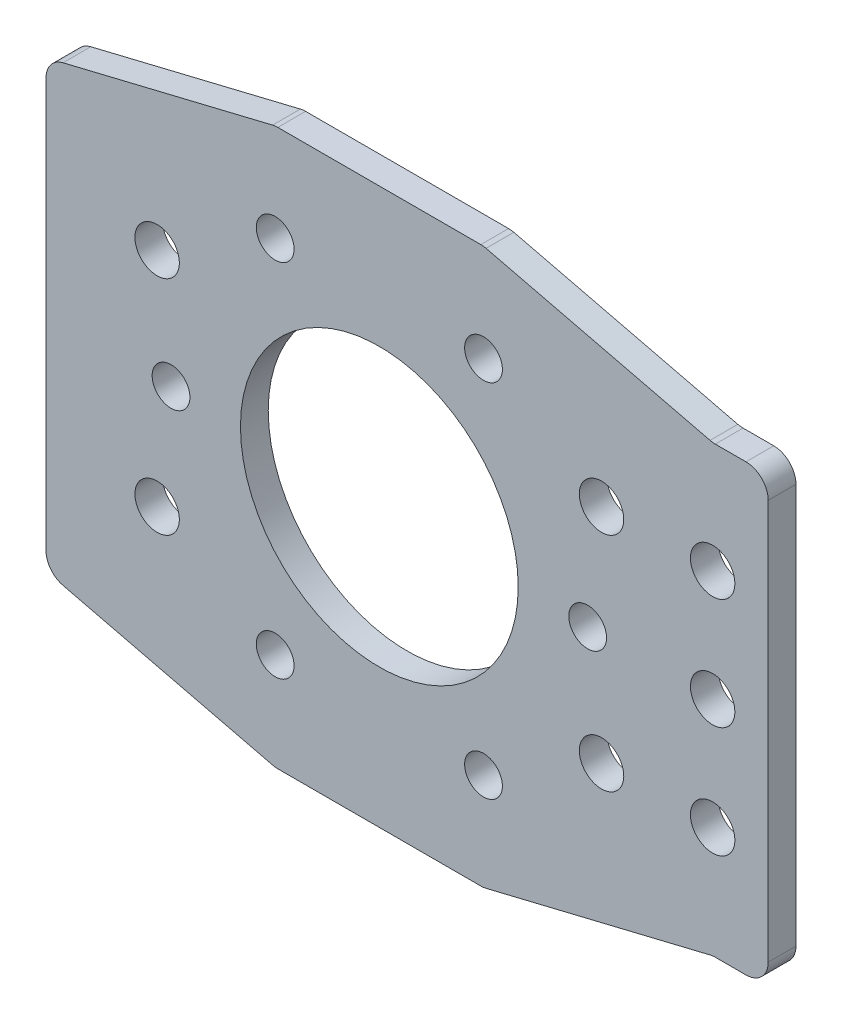
SolidWorks part; units mm, degrees
ref_plane "Front Plane" through (0, 0, 0) normal (0, 0, 1) x (1, 0, 0)
ref_plane "Top Plane" through (0, 0, 0) normal (0, 1, 0) x (1, 0, 0)
ref_plane "Right Plane" through (0, 0, 0) normal (1, 0, 0) x (0, 0, -1)
sketch "Sketch1" plane through (0, 0, 0) normal (0, 0, 1) x (1, 0, 0)
  arc A19 (-480.6, -14.2) -> (-459.2, -14.2) centre (-469.9, 0) ccw
  arc A20 (-446.9968, 12.573) -> (-442.0032, 12.573) centre (-444.5, 12.7) ccw
  arc A21 (-421.5968, 12.573) -> (-416.6032, 12.573) centre (-419.1, 12.7) ccw
  arc A22 (-434.2968, 12.573) -> (-429.3032, 12.573) centre (-431.8, 12.7) ccw
  arc A23 (-434.2968, -0.127) -> (-429.3032, -0.127) centre (-431.8, 0) ccw
  arc A24 (-421.5968, -0.127) -> (-416.6032, -0.127) centre (-419.1, 0) ccw
  arc A25 (-421.5968, -12.827) -> (-416.6032, -12.827) centre (-419.1, -12.7) ccw
  arc A26 (-434.2968, -12.827) -> (-429.3032, -12.827) centre (-431.8, -12.7) ccw
  arc A27 (-446.9968, -12.827) -> (-442.0032, -12.827) centre (-444.5, -12.7) ccw
  arc A28 (-491.5572, 0.127) -> (-494.0059, 2.139) centre (-493.7125, 0) ccw
  arc A29 (-494.0059, -2.139) -> (-491.5572, -0.127) centre (-493.7125, 0) ccw
  arc A30 (-497.7968, 12.573) -> (-492.8032, 12.573) centre (-495.3, 12.7) ccw
  arc A31 (-497.7968, -12.827) -> (-492.8032, -12.827) centre (-495.3, -12.7) ccw
  circle A32 centre (-481.8062, -20.6222) radius 2.159
  circle A33 centre (-457.9938, -20.6222) radius 2.159
  arc A34 (-448.2428, -0.127) -> (-445.7941, -2.139) centre (-446.0875, 0) ccw
  arc A35 (-445.7941, 2.139) -> (-448.2428, 0.127) centre (-446.0875, 0) ccw
  circle A36 centre (-457.9937, 20.6222) radius 2.159
  circle A37 centre (-481.8063, 20.6222) radius 2.159
sketch "Sketch2" plane through (0, 0, 0) normal (0, 0, 1) x (1, 0, 0)
  line L0 (-508, 25.4) -> (-481.8062, 31.75)
  line L1 (-481.8062, 31.75) -> (-457.9937, 31.75)
  line L2 (-457.9937, 31.75) -> (-431.8, 25.4)
  line L3 (-431.8, 25.4) -> (-368.3, 25.4)
  line L4 (-368.3, 25.4) -> (-368.3, -25.4)
  line L5 (-368.3, -25.4) -> (-431.8, -25.4)
  line L6 (-431.8, -25.4) -> (-457.9937, -31.75)
  line L7 (-457.9937, -31.75) -> (-481.8062, -31.75)
  line L8 (-481.8062, -31.75) -> (-508, -25.4)
  line L9 (-508, 25.4) -> (-508, -25.4)
  line L10 (-419.1, 12.7) -> (-406.4, 12.7) construction
  circle A0 centre (-469.9, 0) radius 15.875
  circle A1 centre (-457.9937, 20.6222) radius 2.159
  circle A2 centre (-481.8063, 20.6222) radius 2.159
  circle A3 centre (-493.7125, 0) radius 2.159
  circle A4 centre (-481.8062, -20.6222) radius 2.159
  circle A5 centre (-457.9938, -20.6222) radius 2.159
  circle A6 centre (-446.0875, 0) radius 2.159
  circle A7 centre (-495.3, 12.7) radius 2.54
  circle A8 centre (-495.3, -12.7) radius 2.54
  circle A9 centre (-444.5, -12.7) radius 2.54
  circle A10 centre (-431.8, -12.7) radius 2.54
  circle A11 centre (-419.1, -12.7) radius 2.54
  circle A12 centre (-419.1, 0) radius 2.54
  circle A13 centre (-431.8, 0) radius 2.54
  circle A14 centre (-431.8, 12.7) radius 2.54
  circle A15 centre (-419.1, 12.7) radius 2.54
  circle A16 centre (-444.5, 12.7) radius 2.54
  circle A17 centre (-406.4, 12.7) radius 2.54
  circle A18 centre (-406.4, 0) radius 2.54
  circle A19 centre (-406.4, -12.7) radius 2.54
  circle A20 centre (-393.7, 12.7) radius 2.54
  circle A21 centre (-393.7, 0) radius 2.54
  circle A22 centre (-393.7, -12.7) radius 2.54
  circle A23 centre (-381, 12.7) radius 2.54
  circle A24 centre (-381, 0) radius 2.54
  circle A25 centre (-381, -12.7) radius 2.54
  dimension "D1" = 4.318
  dimension "D2" = 31.75
  dimension "D3" = 5.08
  dimension "D4" = 50.8
  dimension "D5" = 25.4
  dimension "D6" = 63.5
  dimension "D7" = 6.35
  dimension "D8" = 38.1
  dimension "D9" = 38.1
  dimension "D11" = 12.7
  dimension "D12" = 101.6
  dimension "D13" = 50.8
  dimension "D10" = 4
extrude "Boss-Extrude1" add sketch "Sketch2" along normal blind 3.175
fillet "Fillet1" radius 2.54 10 edges at (-431.8, -25.4, 1.5875) (-457.9937, -31.75, 1.5875) (-481.8062, -31.75, 1.5875) (-481.8062, 31.75, 1.5875) (-457.9937, 31.75, 1.5875) (-431.8, 25.4, 1.5875) (-508, -25.4, 1.5875) (-508, 25.4, 1.5875) (-368.3, -25.4, 1.5875) (-368.3, 25.4, 1.5875)
sketch "Sketch3" plane through (0, 0, 3.175) normal (0, 0, 1) x (1, 0, 0)
  line L0 (-508, 23.4022) -> (-508, -23.4022) construction
  line L1 (-508, 39.539) -> (-425.45, 39.539)
  line L2 (-508, 39.539) -> (-508, -34.5278)
  line L3 (-508, -34.5278) -> (-425.45, -34.5278)
  line L4 (-425.45, 39.539) -> (-425.45, -34.5278)
  dimension "D1" = 82.55
extrude "Cut-Extrude1" cut sketch "Sketch3" against normal through all flip side to cut
fillet "Fillet2" radius 2.54 2 edges at (-425.45, -25.4, 1.5875) (-425.45, 25.4, 1.5875)
